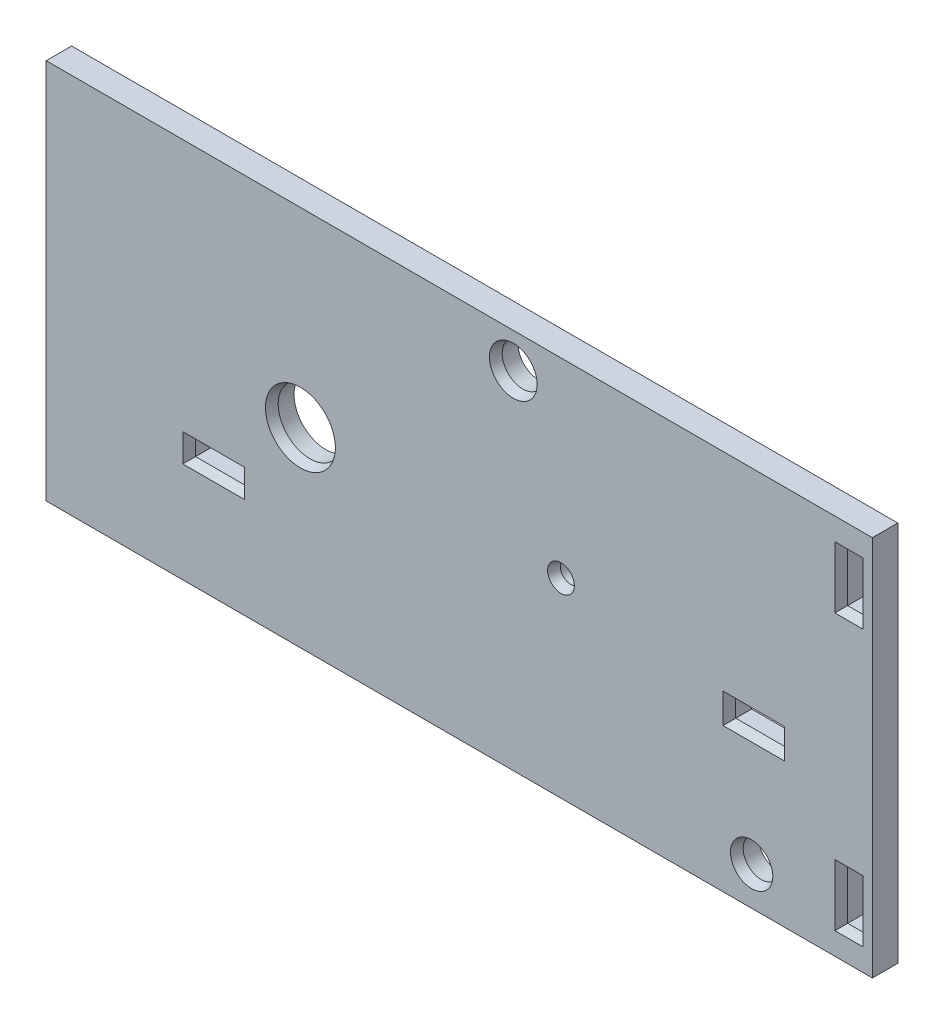
SolidWorks part; units mm, degrees
ref_plane "Front Plane" through (0, 0, 0) normal (0, 0, 1) x (1, 0, 0)
ref_plane "Top Plane" through (0, 0, 0) normal (0, 1, 0) x (1, 0, 0)
ref_plane "Right Plane" through (0, 0, 0) normal (1, 0, 0) x (0, 0, -1)
sketch "Sketch1" plane through (0, 0, 0) normal (0, 0, 1) x (1, 0, 0)
  line L0 (-55.3, -10.3) -> (-55.3, -13.7)
  line L1 (-86, -30) -> (44, -30)
  line L2 (-86, -30) -> (-86, 30)
  line L3 (-86, 30) -> (44, 30)
  line L4 (44, -30) -> (44, 30)
  line L5 (-64, -10.3) -> (-55.3, -10.3)
  line L6 (-64, -10.3) -> (-64, -13.7)
  line L7 (-64, -13.7) -> (-55.3, -13.7)
  line L13 (29.7, -5) -> (21, -5) construction
  line L14 (-55.3, -12) -> (-64, -12) construction
  line L15 (-59.65, -10.3) -> (-59.65, -13.7) construction
  line L16 (40.3, 26) -> (40.3, 17.3) construction
  line L17 (38.6, 26) -> (42, 26)
  line L18 (38.6, 26) -> (38.6, 17.3)
  line L19 (38.6, 17.3) -> (42, 17.3)
  line L20 (42, 26) -> (42, 17.3)
  line L21 (38.6, -17.3) -> (42, -17.3)
  line L22 (38.6, -17.3) -> (38.6, -26)
  line L23 (38.6, -26) -> (42, -26)
  line L24 (42, -17.3) -> (42, -26)
  line L25 (42, 21.65) -> (38.6, 21.65) construction
  line L26 (40.3, -17.3) -> (40.3, -26) construction
  line L27 (42, -21.65) -> (38.6, -21.65) construction
  line L28 (21, -3.15) -> (29.7, -3.15)
  line L29 (21, -3.15) -> (21, -6.85)
  line L30 (21, -6.85) -> (29.7, -6.85)
  line L31 (29.7, -3.15) -> (29.7, -6.85)
  line L32 (25.35, -6.85) -> (25.35, -3.15) construction
  circle A2 centre (-46, 0) radius 5
  circle A3 centre (-12.5, 24.5) radius 3.25
  circle A4 centre (25, -24) radius 2.83
  circle A5 centre (-5, 0) radius 1.6
  point P1 (0, 0)
  point P24 (-86, 0)
  dimension "D10" = 6.5
  dimension "D14" = 5.66
  dimension "D21" = 10
  dimension "D2" = 60
  dimension "D4" = 130
  dimension "D6" = 8.7
  dimension "D8" = 3.4
  dimension "D12" = 111
  dimension "D19" = 24.5
  dimension "D13" = 24
  dimension "D5" = 40
  dimension "D7" = 33.5
  dimension "D9" = 7.5
  dimension "D11" = 26.35
  dimension "D15" = 126.3
  dimension "D17" = 21.65
  dimension "D18" = 21.65
  dimension "D16" = 85
  dimension "D3" = 5
  dimension "D20" = 12
extrude "Boss-Extrude1" add sketch "Sketch1" along normal mid plane 4
sketch "Sketch2" plane through (0, 0, 2) normal (0, 0, 1) x (1, 0, 0)
  line L0 (40.3, 26) -> (40.3, 17.3) construction
  line L1 (42, 21.65) -> (38.6, 21.65) construction
  line L2 (40.3, -17.3) -> (40.3, -26) construction
  line L3 (42, -17.3) -> (38.6, -17.3) construction
  line L4 (38.6, -26) -> (42, -26) construction
  line L5 (38.6, -21.65) -> (42, -21.65) construction
  line L6 (38.6, -17.3) -> (38.6, -26) construction
  line L7 (42, -26) -> (42, -17.3) construction
sketch "Sketch4" plane through (0, 0, -2) normal (0, 0, -1) x (-1, 0, 0)
  line L0 (59.65, -10.3) -> (59.65, -13.7) construction
  line L1 (55.3, -12) -> (64, -12) construction
  line L2 (-29.7, -5) -> (-21, -5) construction
  line L3 (-29.7, -6.85) -> (-29.7, -3.15) construction
  line L4 (-21, -3.15) -> (-21, -6.85) construction
  line L5 (-25.35, -3.15) -> (-25.35, -6.85) construction
  line L6 (-29.7, -3.15) -> (-21, -3.15) construction
  line L7 (-21, -6.85) -> (-29.7, -6.85) construction
chamfer "Chamfer1" distance 0.5 distance2 1.5 20 edges at (40.3, -26, 2) (42, -21.65, 2) (40.3, -17.3, 2) (38.6, -21.65, 2) (-3.4, 0, 2) (27.83, -24, 2) (-41, 0, 2) (-9.25, 24.5, 2) (-59.65, -13.7, 2) (-55.3, -12, 2) (-59.65, -10.3, 2) (-64, -12, 2) (25.35, -6.85, 2) (29.7, -5, 2) (25.35, -3.15, 2) (21, -5, 2) (40.3, 17.3, 2) (42, 21.65, 2) (40.3, 26, 2) (38.6, 21.65, 2)
equation "\"padding\"=4"
equation "\"hole_width\"=3.4"
equation "\"hole_height\"=8.7"
equation "\"back_boost\"= 7"
equation "\"D5@Sketch1\"=33+\"back_boost\""
equation "\"D12@Sketch1\"=104+\"back_boost\""
equation "\"D15@Sketch1\"=119.30mm+\"back_boost\""
equation "\"D11@Sketch1\"=\"back_boost\"+19.35mm"
equation "\"D4@Sketch1\"=\"back_boost\"+123.00mm"
equation "\"pin_hole_height\"=9.2"
equation "\"pin_hole_width\"=3.53"
